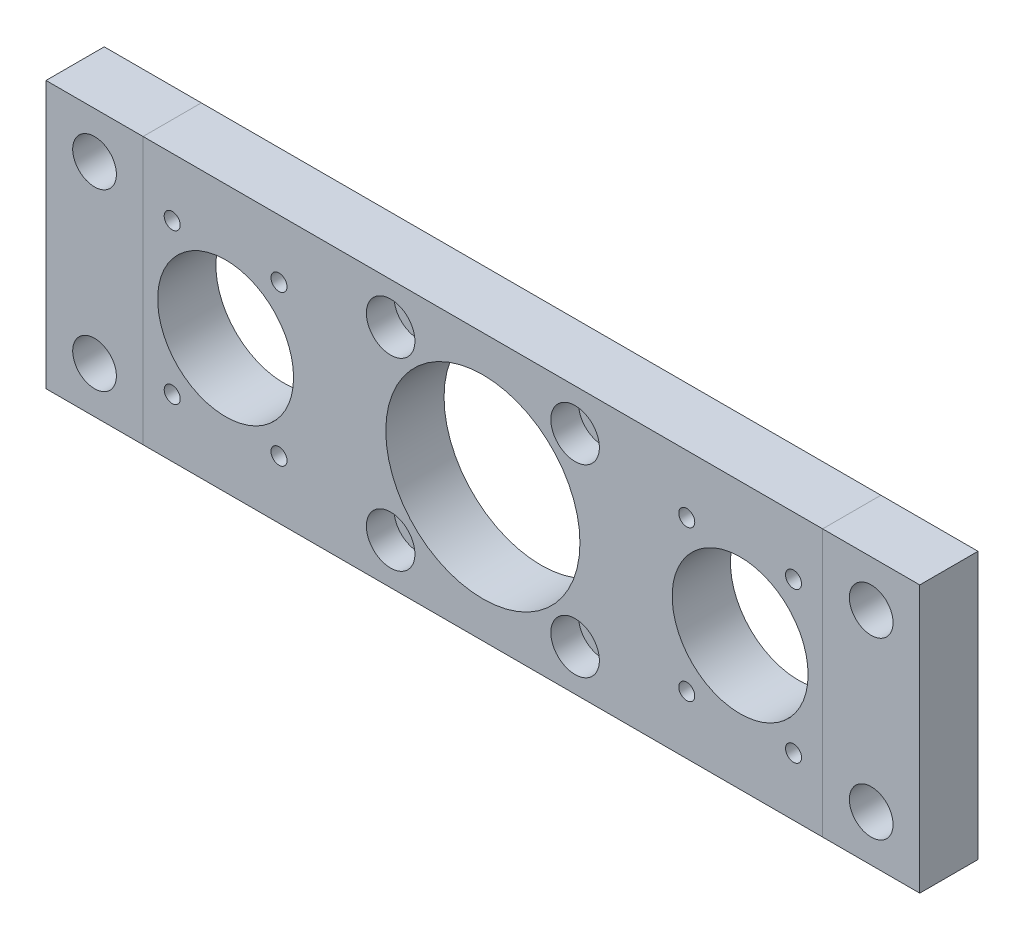
SolidWorks part; units mm, degrees
ref_plane "Front" through (0, 0, 0) normal (0, 0, 1) x (1, 0, 0)
ref_plane "Top" through (0, 0, 0) normal (0, 1, 0) x (1, 0, 0)
ref_plane "Right" through (0, 0, 0) normal (1, 0, 0) x (0, 0, -1)
sketch "草图1" plane through (0, 0, 0) normal (0, 0, 1) x (1, 0, 0)
  line L1 (-70, -27.5) -> (70, -27.5)
  line L2 (-70, -27.5) -> (-70, 27.5)
  line L3 (-70, 27.5) -> (70, 27.5)
  line L4 (70, -27.5) -> (70, 27.5)
  line L5 (-70, -27.5) -> (70, 27.5) construction
  line L6 (-70, 27.5) -> (70, -27.5) construction
  point P0 (0, 0)
  dimension "D1" = 55
  dimension "D2" = 140
extrude "凸台-拉伸1" add sketch "草图1" along normal blind 12
sketch "草图2" plane through (0, 0, 12) normal (0, 0, 1) x (1, 0, 0)
  line L0 (-70, 27.5) -> (-70, -27.5) construction
  line L1 (70, -27.5) -> (70, 27.5) construction
  circle A0 centre (0, 0) radius 20
  circle A1 centre (-53, 0) radius 14
  circle A2 centre (53, 0) radius 14
  dimension "D1" = 40
  dimension "D2" = 28
  dimension "D3" = 28
  dimension "D4" = 17
  dimension "D5" = 17
extrude "切除-拉伸1" cut sketch "草图2" against normal through all
sketch "草图3" plane through (0, 0, 12) normal (0, 0, 1) x (1, 0, 0)
  line L1 (-64, -15.5) -> (-42, -15.5) construction
  line L2 (-64, -15.5) -> (-64, 15.5) construction
  line L3 (-64, 15.5) -> (-42, 15.5) construction
  line L4 (-42, -15.5) -> (-42, 15.5) construction
  line L5 (-64, -15.5) -> (-42, 15.5) construction
  line L6 (-64, 15.5) -> (-42, -15.5) construction
  line L7 (42, -15.5) -> (64, -15.5) construction
  line L8 (42, -15.5) -> (42, 15.5) construction
  line L9 (42, 15.5) -> (64, 15.5) construction
  line L10 (64, -15.5) -> (64, 15.5) construction
  line L11 (42, -15.5) -> (64, 15.5) construction
  line L12 (42, 15.5) -> (64, -15.5) construction
  point P0 (-53, 0)
  point P6 (53, 0)
  dimension "D1" = 22
  dimension "D2" = 31
  dimension "D3" = 22
  dimension "D4" = 31
hole_wizard "M4 螺纹孔1" positions "草图4" profile "草图5" tap size "M4" standard "GB" end condition through all
sketch "草图4" plane through (0, 0, 12) normal (0, 0, 1) x (1, 0, 0)
  point P0 (-64, 15.5)
  point P3 (-42, 15.5)
  point P6 (-42, -15.5)
  point P9 (-64, -15.5)
  point P12 (42, -15.5)
  point P15 (64, -15.5)
  point P18 (64, 15.5)
  point P21 (42, 15.5)
sketch "草图5" plane through (-64, 15.5, 12) normal (1, 0, 0) x (0, -1, 0)
  line L0 (0, 0) -> (0, 12)
  line L1 (0, 12) -> (1.65, 12)
  line L2 (1.65, 12) -> (1.65, 0)
  line L5 (1.65, 0) -> (0, 0)
  line L11 (0, -6.35) -> (0, 107.95) construction
  dimension "通孔螺纹孔钻头直径" = 3.3
  dimension "通孔螺纹孔钻头深度" = 12
cosmetic thread "孔螺蚊线1" parameters "D2"=4
cosmetic thread "孔螺蚊线2" parameters "D2"=4
cosmetic thread "孔螺蚊线3" parameters "D2"=4
cosmetic thread "孔螺蚊线4" parameters "D2"=4
cosmetic thread "孔螺蚊线5" parameters "D2"=4
cosmetic thread "孔螺蚊线6" parameters "D2"=4
cosmetic thread "孔螺蚊线7" parameters "D2"=4
cosmetic thread "孔螺蚊线8" parameters "D2"=4
sketch "草图6" plane through (0, 0, 12) normal (0, 0, 1) x (1, 0, 0)
  line L1 (-19, -19) -> (19, -19) construction
  line L2 (-19, -19) -> (-19, 19) construction
  line L3 (-19, 19) -> (19, 19) construction
  line L4 (19, -19) -> (19, 19) construction
  line L5 (-19, -19) -> (19, 19) construction
  line L6 (-19, 19) -> (19, -19) construction
  point P0 (0, 0)
  dimension "D1" = 38
  dimension "D2" = 38
hole_wizard "打孔尺寸(%根据)内六角圆柱头螺钉的类型1" positions "草图7" profile "草图9" counterbore size "M5" standard "GB" end condition through all
sketch "草图7" plane through (0, 0, 12) normal (0, 0, 1) x (1, 0, 0)
  point P0 (-19, 19)
  point P3 (19, 19)
  point P6 (19, -19)
  point P9 (-19, -19)
sketch "草图9" plane through (-19, 19, 12) normal (1, 0, 0) x (0, -1, 0)
  line L0 (0, 0) -> (0, 12)
  line L1 (0, 12) -> (2.75, 12)
  line L3 (2.75, 12) -> (2.75, 5.7)
  line L4 (2.75, 5.7) -> (5, 5.7)
  line L5 (5, 5.7) -> (5, 0)
  line L7 (5, 0) -> (0, 0)
  line L11 (0, -6.35) -> (0, 107.95) construction
  dimension "通孔孔直径" = 5.5
  dimension "通孔孔深度" = 12
  dimension "柱形沉头孔直径" = 10
  dimension "柱形沉头孔深度" = 5.7
sketch "草图10" plane through (0, 0, 12) normal (0, 0, 1) x (1, 0, 0)
  line L1 (70, 27.5) -> (90, 27.5)
  line L2 (70, 27.5) -> (70, -27.5)
  line L3 (70, -27.5) -> (90, -27.5)
  line L4 (90, 27.5) -> (90, -27.5)
  line L5 (-70, 27.5) -> (-90, 27.5)
  line L6 (-70, 27.5) -> (-70, -27.5)
  line L7 (-70, -27.5) -> (-90, -27.5)
  line L8 (-90, 27.5) -> (-90, -27.5)
  line L9 (-80, -18) -> (80, -18) construction
  line L10 (-80, -18) -> (-80, 18) construction
  line L11 (-80, 18) -> (80, 18) construction
  line L12 (80, -18) -> (80, 18) construction
  line L13 (-80, -18) -> (80, 18) construction
  line L14 (-80, 18) -> (80, -18) construction
  circle A0 centre (-80, 18) radius 4.5
  circle A1 centre (-80, -18) radius 4.5
  circle A2 centre (80, -18) radius 4.5
  circle A3 centre (80, 18) radius 4.5
  point P10 (0, 0)
  dimension "D5" = 9
  dimension "D6" = 9
  dimension "D7" = 9
  dimension "D8" = 9
  dimension "D1" = 20
  dimension "D2" = 20
  dimension "D3" = 160
  dimension "D4" = 36
extrude "凸台-拉伸2" add sketch "草图10" against normal blind 12 separate body
